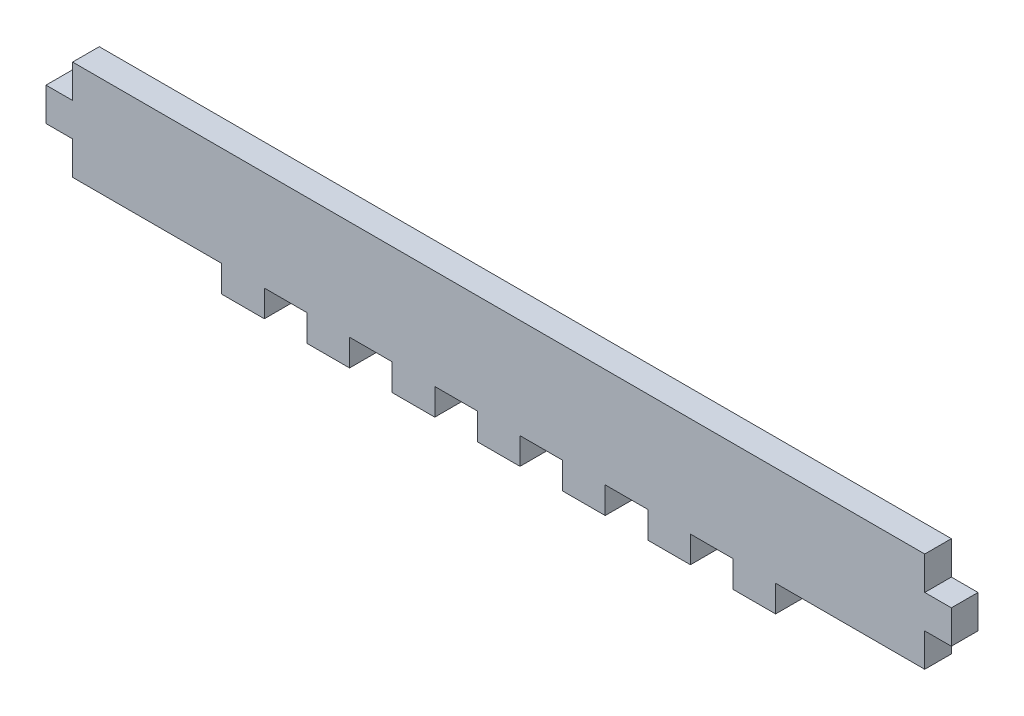
SolidWorks part; units mm, degrees
ref_plane "Front Plane" through (0, 0, 0) normal (0, 0, 1) x (1, 0, 0)
ref_plane "Top Plane" through (0, 0, 0) normal (0, 1, 0) x (1, 0, 0)
ref_plane "Right Plane" through (0, 0, 0) normal (1, 0, 0) x (0, 0, -1)
sketch "Sketch1" plane through (0, 0, 0) normal (0, 0, 1) x (1, 0, 0)
  line L0 (-53.975, 1.9844) -> (-53.975, 5.9531) construction
  line L1 (-50.8, -5.9531) -> (-33.02, -5.9531)
  line L2 (-53.975, -1.9844) -> (-53.975, 1.9844)
  line L3 (-50.8, 5.9531) -> (50.8, 5.9531)
  line L4 (50.8, -5.9531) -> (53.975, -5.9531) construction
  line L5 (-53.975, -5.9531) -> (53.975, 5.9531) construction
  line L6 (-53.975, 5.9531) -> (53.975, -5.9531) construction
  line L7 (-53.975, 1.9844) -> (-50.8, 1.9844)
  line L8 (-53.975, 5.9531) -> (-50.8, 5.9531) construction
  line L9 (-53.975, -1.9844) -> (-53.975, -5.9531) construction
  line L10 (-50.8, 1.9844) -> (-50.8, 5.9531)
  line L11 (-53.975, -1.9844) -> (-50.8, -1.9844)
  line L12 (-53.975, -5.9531) -> (-50.8, -5.9531) construction
  line L13 (0, -5.9531) -> (0, 5.9531) construction
  line L14 (-50.8, -1.9844) -> (-50.8, -5.9531)
  line L15 (50.8, 5.9531) -> (53.975, 5.9531) construction
  line L16 (53.975, -1.9844) -> (53.975, -5.9531) construction
  line L17 (-27.94, -5.9531) -> (-22.86, -5.9531)
  line L18 (53.975, 1.9844) -> (53.975, 5.9531) construction
  line L19 (50.8, -1.9844) -> (50.8, -5.9531)
  line L20 (53.975, -1.9844) -> (50.8, -1.9844)
  line L21 (50.8, 1.9844) -> (50.8, 5.9531)
  line L22 (53.975, 1.9844) -> (50.8, 1.9844)
  line L23 (53.975, -1.9844) -> (53.975, 1.9844)
  line L24 (-22.86, -5.9531) -> (-22.86, -9.1281)
  line L25 (-33.02, -5.9531) -> (-33.02, -9.1281)
  line L26 (-33.02, -9.1281) -> (-27.94, -9.1281)
  line L27 (-27.94, -5.9531) -> (-27.94, -9.1281)
  line L28 (-22.86, -9.1281) -> (-17.78, -9.1281)
  line L29 (-17.78, -5.9531) -> (-17.78, -9.1281)
  line L30 (-12.7, -5.9531) -> (-12.7, -9.1281)
  line L31 (-12.7, -9.1281) -> (-7.62, -9.1281)
  line L32 (-7.62, -5.9531) -> (-7.62, -9.1281)
  line L33 (-2.54, -5.9531) -> (-2.54, -9.1281)
  line L34 (-2.54, -9.1281) -> (2.54, -9.1281)
  line L35 (2.54, -5.9531) -> (2.54, -9.1281)
  line L36 (7.62, -5.9531) -> (7.62, -9.1281)
  line L37 (7.62, -9.1281) -> (12.7, -9.1281)
  line L38 (12.7, -5.9531) -> (12.7, -9.1281)
  line L39 (17.78, -5.9531) -> (17.78, -9.1281)
  line L40 (17.78, -9.1281) -> (22.86, -9.1281)
  line L41 (22.86, -5.9531) -> (22.86, -9.1281)
  line L42 (27.94, -5.9531) -> (27.94, -9.1281)
  line L43 (27.94, -9.1281) -> (33.02, -9.1281)
  line L44 (33.02, -5.9531) -> (33.02, -9.1281)
  line L45 (33.02, -5.9531) -> (50.8, -5.9531)
  line L46 (-17.78, -5.9531) -> (-12.7, -5.9531)
  line L47 (-7.62, -5.9531) -> (-2.54, -5.9531)
  line L48 (2.54, -5.9531) -> (7.62, -5.9531)
  line L49 (12.7, -5.9531) -> (17.78, -5.9531)
  line L50 (22.86, -5.9531) -> (27.94, -5.9531)
  line L51 (-2.54, -5.9531) -> (2.54, -5.9531) construction
  point P0 (0, 0)
  point P15 (0, 0)
  dimension "D1" = 11.9062
  dimension "D2" = 107.95
  dimension "D3" = 3.175
  dimension "D4" = 5.08
  dimension "D5" = 3.175
  dimension "D6" = 7
extrude "Boss-Extrude1" add sketch "Sketch1" along normal blind 3.175
